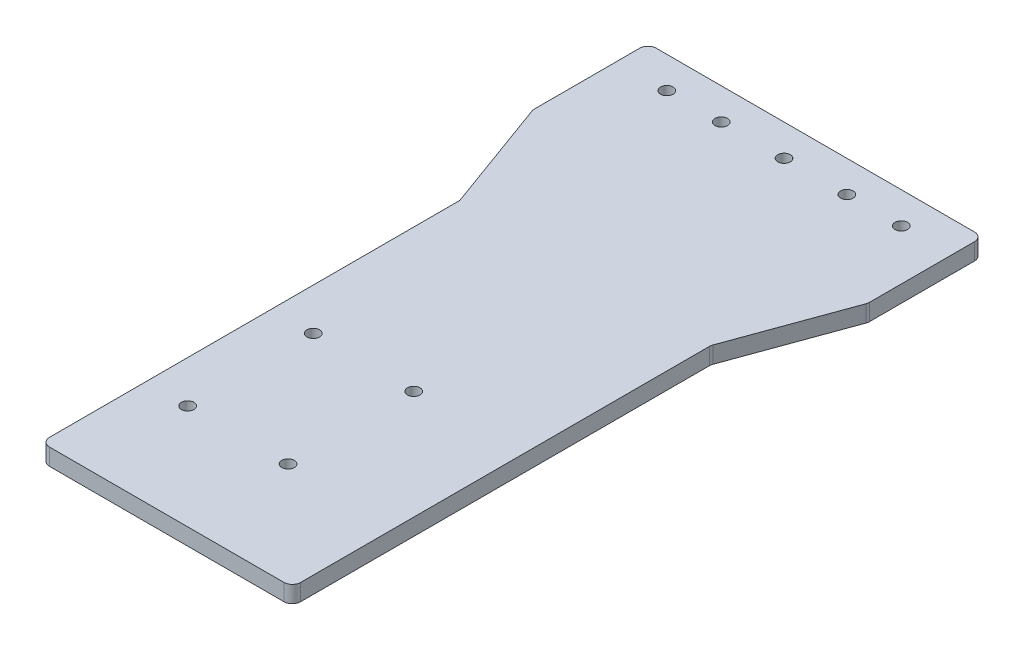
SolidWorks part; units mm, degrees
ref_plane "前视基准面" through (0, 0, 0) normal (0, 0, 1) x (1, 0, 0)
ref_plane "上视基准面" through (0, 0, 0) normal (0, 1, 0) x (1, 0, 0)
ref_plane "右视基准面" through (0, 0, 0) normal (1, 0, 0) x (0, 0, -1)
sketch "草图1" plane through (0, 0, 0) normal (0, 1, 0) x (1, 0, 0)
  line L0 (-0.1206, 100.3314) -> (-9.8794, 127.1434)
  line L1 (2, 0) -> (58, 0)
  line L2 (0, 2) -> (0, 99.6473)
  line L3 (30, 166.4236) -> (30, 127.3917) construction
  line L4 (60, 2) -> (60, 99.6473)
  line L5 (-8, 154.9495) -> (68, 154.9495)
  line L6 (69.8794, 127.1434) -> (60.1206, 100.3314)
  line L7 (-10, 152.9495) -> (-10, 127.8274)
  line L8 (70, 152.9495) -> (70, 127.8274)
  arc A0 (60.1206, 100.3314) -> (60, 99.6473) centre (62, 99.6473) ccw
  arc A1 (0, 99.6473) -> (-0.1206, 100.3314) centre (-2, 99.6473) ccw
  arc A2 (2, 0) -> (0, 2) centre (2, 2) cw
  arc A3 (58, 0) -> (60, 2) centre (58, 2) ccw
  arc A4 (69.8794, 127.1434) -> (70, 127.8274) centre (68, 127.8274) ccw
  arc A5 (70, 152.9495) -> (68, 154.9495) centre (68, 152.9495) ccw
  arc A6 (-10, 152.9495) -> (-8, 154.9495) centre (-8, 152.9495) cw
  arc A7 (-9.8794, 127.1434) -> (-10, 127.8274) centre (-8, 127.8274) cw
  point P9 (60, 100)
  point P12 (0, 100)
  point P15 (0, 0)
  point P20 (80, 154.9495)
  point P22 (70, 154.9495)
  point P23 (-20, 154.9495)
  point P31 (-10, 154.9495)
  dimension "D6" = 2
  dimension "D8" = 2
  dimension "D1" = 100
  dimension "D2" = 60
  dimension "D3" = 160
  dimension "D4" = 100
  dimension "D5" = 160
  dimension "D7" = 40
extrude "凸台-拉伸1" add sketch "草图1" along normal blind 4
sketch "草图2" plane through (0, 4, 0) normal (0, 1, 0) x (1, 0, 0)
  line L0 (2, 0) -> (58, 0) construction
  line L1 (0, 99.6473) -> (0, 2) construction
  circle A0 centre (10, 25) radius 1.5
  circle A1 centre (34, 25) radius 1.5
  circle A2 centre (34, 55) radius 1.5
  circle A3 centre (10, 55) radius 1.5
  dimension "D1" = 25
  dimension "D2" = 10
  dimension "D3" = 2
  dimension "D4" = 2
extrude "切除-拉伸1" cut sketch "草图2" against normal blind 4
sketch "草图3" plane through (0, 4, 0) normal (0, 1, 0) x (1, 0, 0)
  line L0 (30, 166.8588) -> (30, -16.6645) construction
  line L1 (68, 154.9495) -> (-8, 154.9495) construction
  circle A0 centre (2, 147.4495) radius 1.5
  circle A1 centre (15, 147.4495) radius 1.5
  circle A2 centre (45, 147.4495) radius 1.5
  circle A3 centre (58, 147.4495) radius 1.5
  circle A4 centre (30, 147.4495) radius 1.5
  point P8 (30, 154.9495)
  dimension "D1" = 7.5
  dimension "D2" = 13
  dimension "D3" = 15
  dimension "D4" = 0
extrude "切除-拉伸2" cut sketch "草图3" against normal blind 4
